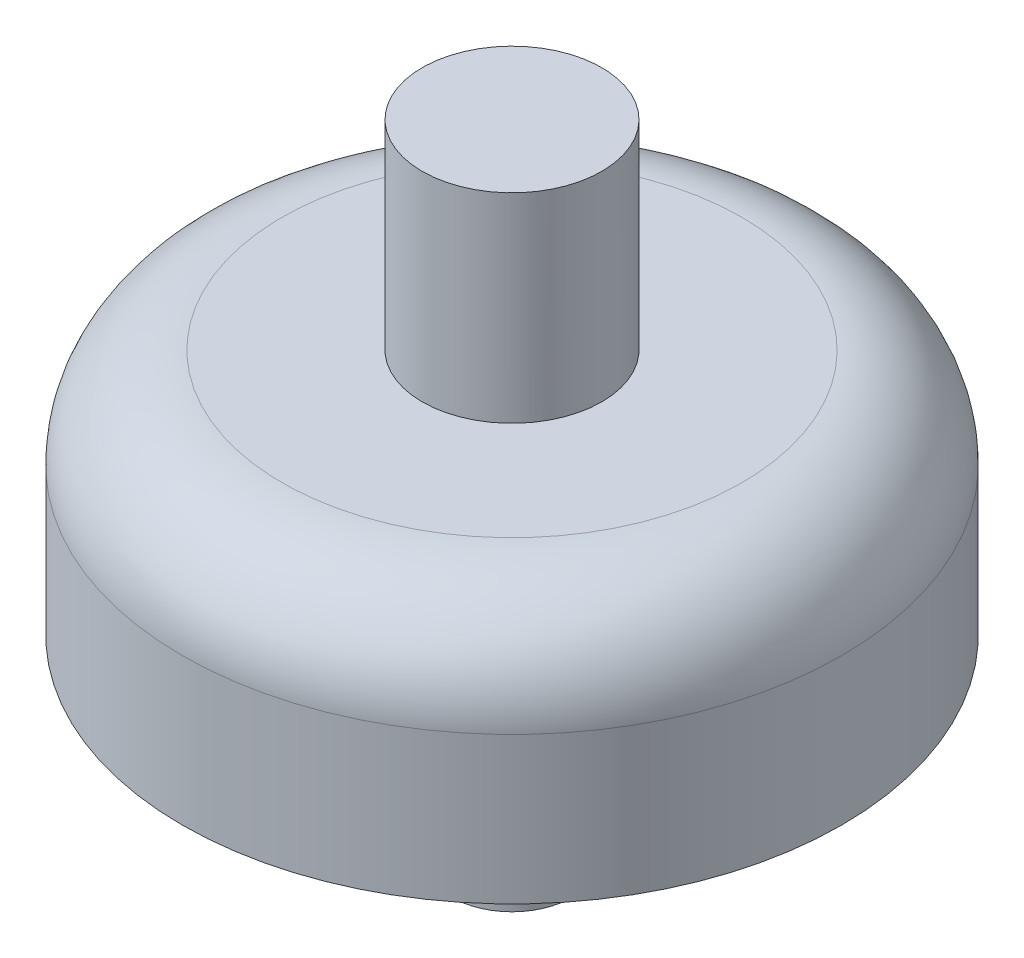
SolidWorks part; units mm, degrees
ref_plane "Front Plane" through (0, 0, 0) normal (0, 0, 1) x (1, 0, 0)
ref_plane "Top Plane" through (0, 0, 0) normal (0, 1, 0) x (1, 0, 0)
ref_plane "Right Plane" through (0, 0, 0) normal (1, 0, 0) x (0, 0, -1)
sketch "Sketch1" plane through (0, 0, 0) normal (0, 0, 1) x (1, 0, 0)
  line L0 (0, 12.3531) -> (16.5186, 12.3531)
  line L1 (0, 0) -> (16.5186, 0)
  line L2 (0, 0) -> (0, 12.3531)
  line L4 (16.5186, 0) -> (16.5186, 12.3531)
revolve "Revolve1" add sketch "Sketch1" angle 360 about L4
sketch "Sketch3" plane through (0, 12.3531, 0) normal (0, 1, 0) x (1, 0, 0)
  circle A0 centre (16.5186, 0) radius 4.5
  dimension "D1" = 9
extrude "Boss-Extrude1" add sketch "Sketch3" along normal blind 10 and the other way blind 18
fillet "Fillet1" radius 5 1 edges at (16.5186, 12.3531, -16.5186)
sketch "Sketch4" plane through (0, 0, 0) normal (0, -1, 0) x (1, 0, 0)
  line L0 (16.5186, -16.5186) -> (16.5186, 16.5186) construction
  line L1 (33.0372, 0) -> (0, 0) construction
  line L2 (16.5186, 0) -> (9.7601, 6.7585)
  line L3 (16.5186, 0) -> (23.4196, -6.901)
  line L4 (9.6176, -6.901) -> (23.4196, 6.901)
  circle A0 centre (16.5186, 0) radius 16.5186 construction
  circle A1 centre (16.5186, 0) radius 9.7594
  circle A2 centre (9.7601, 6.7585) radius 3
  circle A3 centre (23.4196, 6.901) radius 3
  circle A4 centre (23.4196, -6.901) radius 3
  circle A5 centre (9.6176, -6.901) radius 3
  dimension "D4" = 6
  dimension "D5" = 6
  dimension "D6" = 6
  dimension "D7" = 6
  dimension "D1" = 45
  dimension "D2" = 45
  dimension "D3" = 45
extrude "Boss-Extrude2" add sketch "Sketch4" along normal blind 3
scale "Scale2" scale about centroid uniform scaling yes scale factor 1.5
scale "Scale3" scale about centroid uniform scaling yes scale factor 0.7
